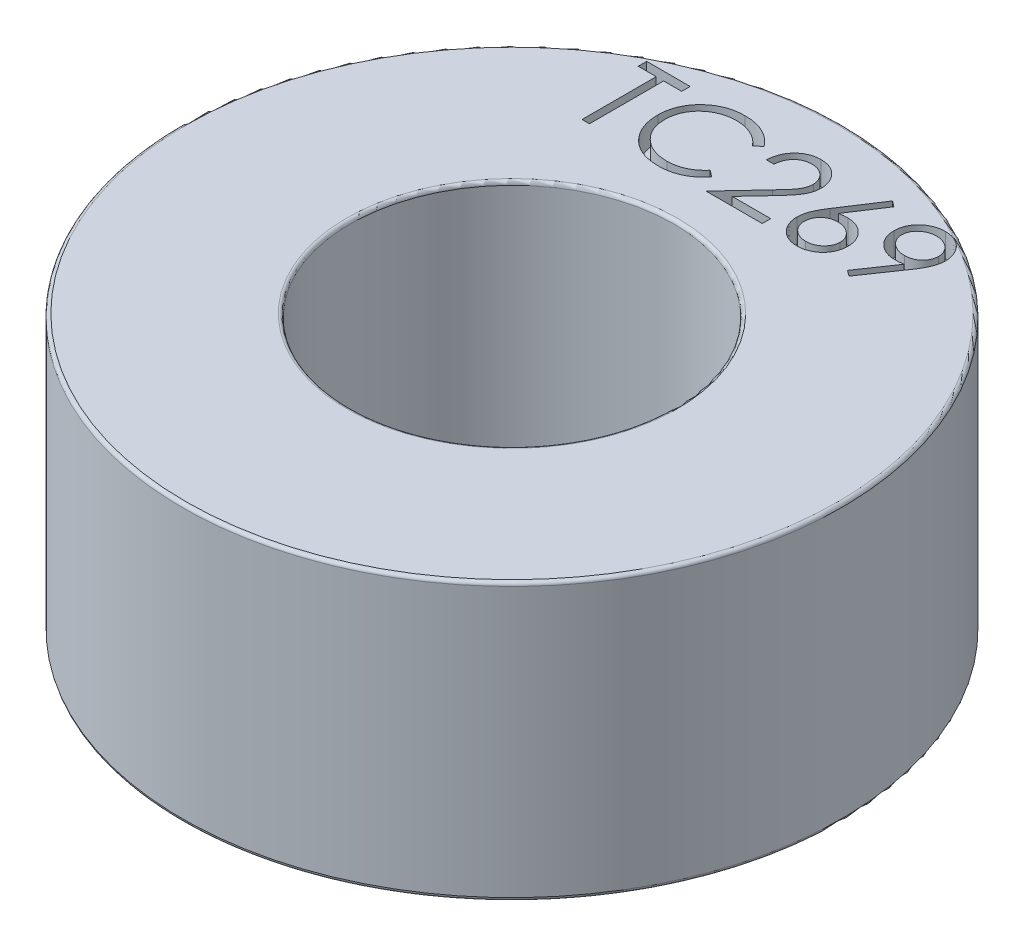
SolidWorks part; units mm, degrees
ref_plane "Front Plane" through (0, 0, 0) normal (0, 0, 1) x (1, 0, 0)
ref_plane "Top Plane" through (0, 0, 0) normal (0, 1, 0) x (1, 0, 0)
ref_plane "Right Plane" through (0, 0, 0) normal (1, 0, 0) x (0, 0, -1)
sketch "Toroidal Core TC269" plane through (0, 0, 0) normal (0, 0, 1) x (1, 0, 0)
  line L0 (0, -8.108) -> (0, 13.3131) construction
  line L2 (6.9961, 0) -> (13.8039, 0)
  line L3 (6.85, 0.1461) -> (6.85, 11.5539)
  line L4 (6.9961, 11.7) -> (13.8039, 11.7)
  line L5 (13.95, 0.1461) -> (13.95, 11.5539)
  arc A0 (6.9961, 0) -> (6.85, 0.1461) centre (6.9961, 0.1461) cw
  arc A1 (13.8039, 0) -> (13.95, 0.1461) centre (13.8039, 0.1461) ccw
  arc A2 (13.8039, 11.7) -> (13.95, 11.5539) centre (13.8039, 11.5539) cw
  arc A3 (6.85, 11.5539) -> (6.9961, 11.7) centre (6.9961, 11.5539) cw
  point P9 (6.85, 0)
  point P12 (13.95, 0)
  point P15 (13.95, 11.7)
  point P18 (6.85, 11.7)
  dimension "D4" = 0.1461
  dimension "D1" = 7.1
  dimension "D2" = 11.7
  dimension "D3" = 6.85
revolve "Revolve2" add sketch "Toroidal Core TC269" angle 360 about L0
sketch "Sketch1" plane through (0, 11.7, 0) normal (0, 1, 0) x (1, 0, 0)
  text T0 "TC269"
extrude "Cut-Extrude1" cut sketch "Sketch1" against normal blind 1
